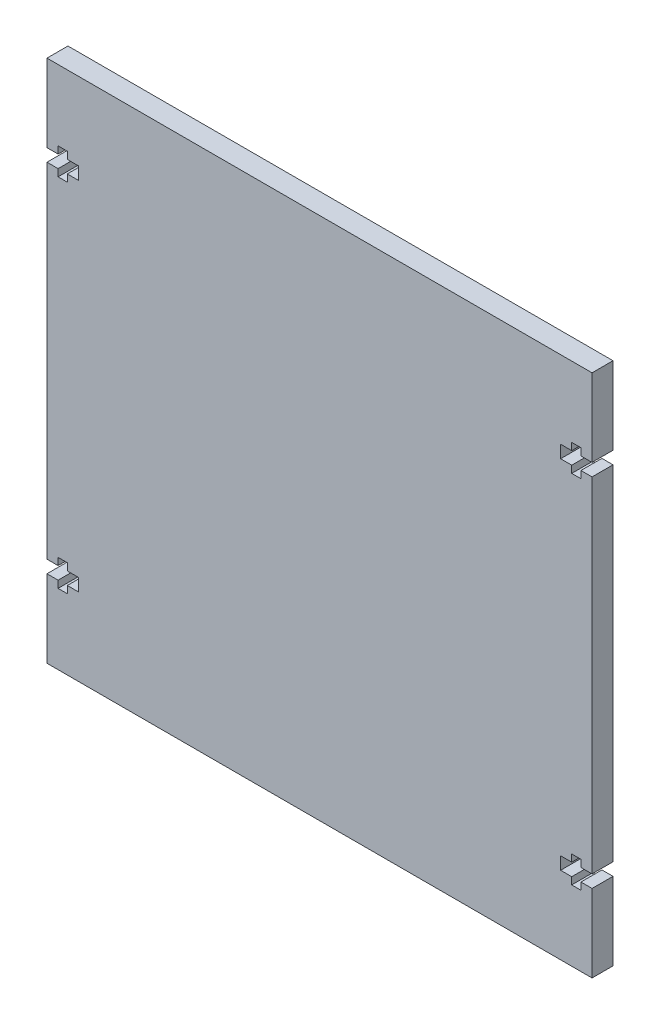
SolidWorks part; units mm, degrees
ref_plane "Front Plane" through (0, 0, 0) normal (0, 0, 1) x (1, 0, 0)
ref_plane "Top Plane" through (0, 0, 0) normal (0, 1, 0) x (1, 0, 0)
ref_plane "Right Plane" through (0, 0, 0) normal (1, 0, 0) x (0, 0, -1)
sketch "Sketch1" plane through (0, 0, 0) normal (0, 0, 1) x (1, 0, 0)
  line L1 (-82.55, -79.375) -> (82.55, -79.375)
  line L2 (-82.55, -79.375) -> (-82.55, 79.375)
  line L3 (-82.55, 79.375) -> (82.55, 79.375)
  line L4 (82.55, -79.375) -> (82.55, 79.375)
  line L5 (-82.55, -79.375) -> (82.55, 79.375) construction
  line L6 (-82.55, 79.375) -> (82.55, -79.375) construction
  point P0 (0, 0)
  dimension "D1" = 165.1
  dimension "D2" = 158.75
extrude "Boss-Extrude2" add sketch "Sketch1" along normal blind 6.35
sketch "Sketch2" plane through (0, 0, 6.35) normal (0, 0, 1) x (1, 0, 0)
  line L0 (-82.55, 0) -> (82.55, 0) construction
  line L1 (82.55, -79.375) -> (82.55, 79.375) construction
  line L2 (82.55, 53.975) -> (-82.55, 53.975) construction
  line L3 (82.55, 79.375) -> (-82.55, 79.375) construction
  line L4 (82.55, 55.88) -> (79.1845, 55.88)
  line L5 (-82.55, 79.375) -> (-82.55, -79.375) construction
  line L6 (82.55, 52.07) -> (79.1845, 52.07)
  line L7 (79.1845, 55.88) -> (79.1845, 58.039)
  line L8 (79.1845, 52.07) -> (79.1845, 49.911)
  line L9 (79.1845, 58.039) -> (76.3905, 58.039)
  line L10 (79.1845, 49.911) -> (76.3905, 49.911)
  line L11 (76.3905, 58.039) -> (76.3905, 55.88)
  line L12 (76.3905, 49.911) -> (76.3905, 52.07)
  line L13 (76.3905, 55.88) -> (73.025, 55.88)
  line L14 (76.3905, 52.07) -> (73.025, 52.07)
  line L15 (73.025, 55.88) -> (73.025, 52.07)
  line L16 (82.55, 55.88) -> (82.55, 52.07)
  point P6 (0, 0)
  point P24 (73.025, 53.975)
  dimension "D1" = 25.4
  dimension "D2" = 3.81
  dimension "D3" = 4.064
  dimension "D4" = 9.525
  dimension "D5" = 2.794
extrude "Cut-Extrude1" cut sketch "Sketch2" against normal through all
mirror "Mirror1" about plane through (0, 0, 0) normal (0, 1, 0) of "Cut-Extrude1"
mirror "Mirror2" about plane through (0, 0, 0) normal (1, 0, 0) of "Cut-Extrude1", "Mirror1"
